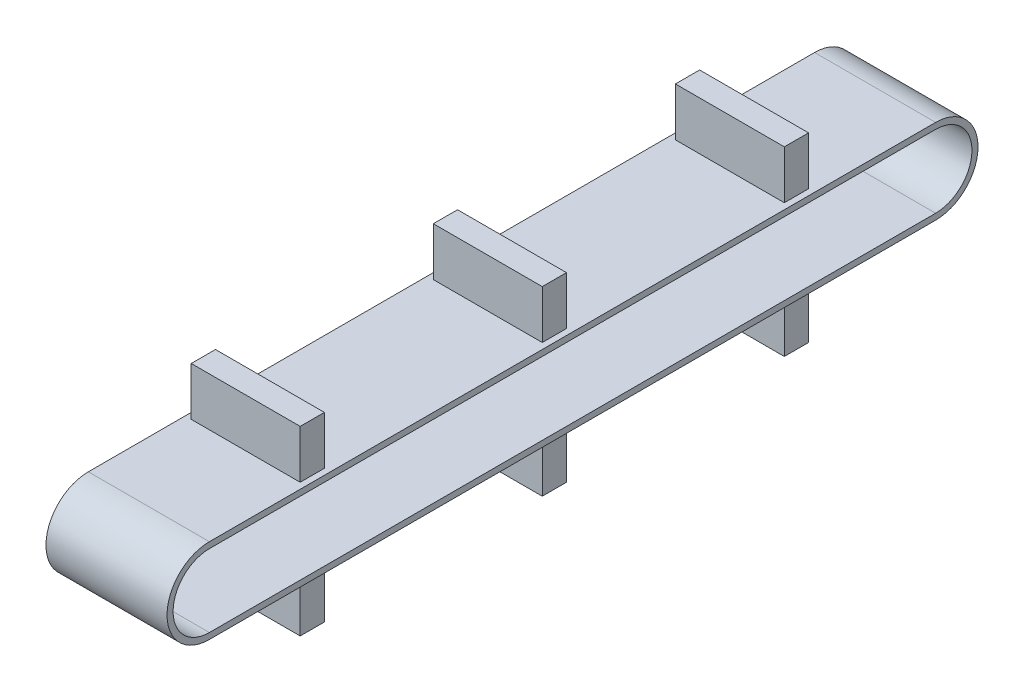
SolidWorks part; units mm, degrees
ref_plane "Alzado" through (0, 0, 0) normal (0, 0, 1) x (1, 0, 0)
ref_plane "Planta" through (0, 0, 0) normal (0, 1, 0) x (1, 0, 0)
ref_plane "Vista lateral" through (0, 0, 0) normal (1, 0, 0) x (0, 0, -1)
sketch "Croquis1" plane through (0, 0, 0) normal (1, 0, 0) x (0, 0, -1)
  line L0 (-54.1795, 17.5) -> (245.8205, 17.5)
  line L1 (-54.1795, -17.5) -> (245.8205, -17.5)
  line L2 (-54.1795, 15) -> (245.8205, 15)
  line L3 (-54.1795, -15) -> (245.8205, -15)
  arc A0 (-54.1795, 17.5) -> (-54.1795, -17.5) centre (-54.1795, 0) ccw
  arc A1 (245.8205, -17.5) -> (245.8205, 17.5) centre (245.8205, 0) ccw
  arc A3 (245.8205, -15) -> (245.8205, 15) centre (245.8205, 0) ccw
  arc A4 (-54.1795, 15) -> (-54.1795, -15) centre (-54.1795, 0) ccw
  dimension "D1" = 35
  dimension "D2" = 30
  dimension "D3" = 300
extrude "Saliente-Extruir1" add sketch "Croquis1" along normal blind 50
sketch "Croquis2" plane through (0, 17.5, 0) normal (0, 1, 0) x (1, 0, 0)
  line L0 (0, 245.8205) -> (0, -54.1795) construction
  line L1 (2.5, 195.8205) -> (47.5, 195.8205)
  line L2 (2.5, 195.8205) -> (2.5, 185.8205)
  line L3 (2.5, 185.8205) -> (47.5, 185.8205)
  line L4 (47.5, 195.8205) -> (47.5, 185.8205)
  line L13 (50, 245.8205) -> (0, 245.8205) construction
  line L14 (2.5, 95.8205) -> (2.5, 85.8205)
  line L15 (2.5, 95.8205) -> (47.5, 95.8205)
  line L16 (47.5, 95.8205) -> (47.5, 85.8205)
  line L17 (2.5, 85.8205) -> (47.5, 85.8205)
  line L18 (2.5, -4.1795) -> (2.5, -14.1795)
  line L19 (2.5, -4.1795) -> (47.5, -4.1795)
  line L20 (47.5, -4.1795) -> (47.5, -14.1795)
  line L21 (2.5, -14.1795) -> (47.5, -14.1795)
  point P4 (2.5, 190.8205)
  dimension "D1" = 45
  dimension "D2" = 2.5
  dimension "D3" = 10
  dimension "D4" = 50
  dimension "D5" = 3
extrude "Saliente-Extruir2" add sketch "Croquis2" along normal blind 20
sketch "Croquis3" plane through (0, -17.5, 0) normal (0, -1, 0) x (1, 0, 0)
  line L0 (50, -245.8205) -> (0, -245.8205) construction
  line L15 (2.5, -185.8205) -> (47.5, -185.8205)
  line L16 (2.5, -185.8205) -> (2.5, -195.8205)
  line L17 (2.5, -195.8205) -> (47.5, -195.8205)
  line L18 (47.5, -185.8205) -> (47.5, -195.8205)
  line L19 (0, 54.1795) -> (0, -245.8205) construction
  line L20 (2.5, -85.8205) -> (2.5, -95.8205)
  line L21 (2.5, -85.8205) -> (47.5, -85.8205)
  line L22 (47.5, -85.8205) -> (47.5, -95.8205)
  line L23 (2.5, -95.8205) -> (47.5, -95.8205)
  line L24 (2.5, 14.1795) -> (2.5, 4.1795)
  line L25 (2.5, 14.1795) -> (47.5, 14.1795)
  line L26 (47.5, 14.1795) -> (47.5, 4.1795)
  line L27 (2.5, 4.1795) -> (47.5, 4.1795)
  dimension "D1" = 50
  dimension "D2" = 2.5
  dimension "D3" = 45
  dimension "D4" = 10
  dimension "D5" = 3
extrude "Saliente-Extruir3" add sketch "Croquis3" along normal blind 20
